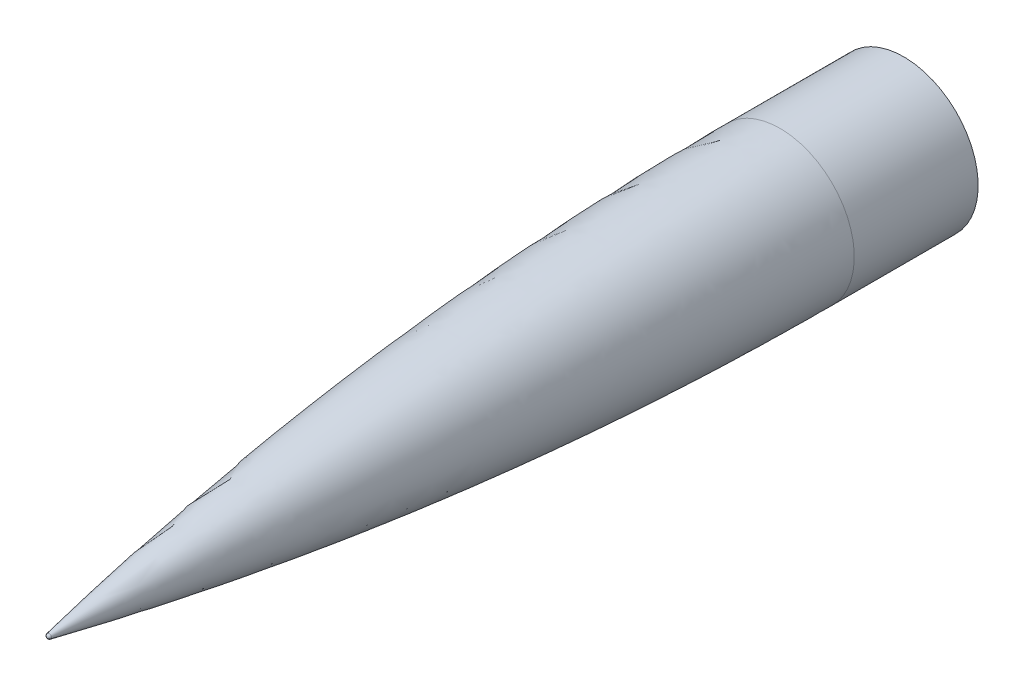
SolidWorks part; units mm, degrees
ref_plane "Front Plane" through (0, 0, 0) normal (0, 0, 1) x (1, 0, 0)
ref_plane "Top Plane" through (0, 0, 0) normal (0, 1, 0) x (1, 0, 0)
ref_plane "Right Plane" through (0, 0, 0) normal (1, 0, 0) x (0, 0, -1)
sketch "Sketch1" plane through (0, 0, 0) normal (1, 0, 0) x (0, 0, -1)
  line L0 (762, 76.2) -> (762, 0)
  line L3 (10.3925, 0) -> (762, 0)
  arc A0 (12.4378, 2.4913) -> (10.3925, 0) centre (12.9325, 0) ccw
  spline S0 degree 4 poles (-61.0191, -12.8425) (-59.4737, -12.5042) (-56.3822, -11.8291) (-51.7403, -10.8208) (-45.5583, -9.4885) (-39.3862, -8.1692) (-33.2692, -6.8717) (-27.1226, -5.5791) (-21.1084, -4.3233) (-14.8868, -3.0366) (-9.0602, -1.8385) (-2.4605, -0.4972) (2.6335, 0.5349) (10.3044, 2.0681) (13.7813, 2.7591) (20.1335, 4.0133) (25.0658, 4.9788) (30.0625, 5.9501) (35.1365, 6.9298) (40.175, 7.8954) (45.2236, 8.856) (50.3004, 9.815) (56.6964, 11.0143) (63.1226, 12.2072) (76.0348, 14.5797) (105.7552, 19.9151) (179.5351, 32.4336) (309.5135, 51.0954) (458.5062, 66.0207) (592.2627, 73.2972) (680.2011, 75.4371) (711.0499, 75.8648) (716.3009, 75.9293) (720.2108, 75.9737) (724.0925, 76.0143) (728.6024, 76.0565) (733.7414, 76.0977) (738.8715, 76.132) (744.039, 76.1594) (749.1296, 76.18) (754.1547, 76.1937) (760.6285, 76.2009) (764.1714, 76.2004) (771.986, 76.1908) (777.1794, 76.1708) (783.9054, 76.1407) (789.8483, 76.1007) (796.194, 76.0506) (802.3313, 75.9905) (808.6051, 75.92) (814.8509, 75.8391) (821.155, 75.7475) (827.4713, 75.6451) (832.2156, 75.5605) (835.3759, 75.5007) (836.956, 75.4699) knots 0 0 0 0 0 0.006999 0.013998 0.020997 0.027996 0.034868 0.041741 0.048613 0.055485 0.062358 0.06923 0.076103 0.082975 0.088656 0.094338 0.100019 0.105701 0.111382 0.117063 0.122745 0.128426 0.134233 0.145846 0.151652 0.186491 0.267783 0.476818 0.732306 0.848437 0.86005 0.865857 0.86876 0.871663 0.877345 0.883026 0.888707 0.894389 0.90007 0.905751 0.911433 0.917114 0.923979 0.930844 0.937709 0.944574 0.951439 0.958304 0.965169 0.972034 0.979026 0.986017 0.993009 1 1 1 1 1 construction
  spline S1 degree 4 poles (12.4378, 2.4913) (13.4887, 2.7001) (15.6066, 3.1195) (20.1335, 4.0133) (25.0658, 4.9788) (30.0625, 5.9501) (35.1365, 6.9298) (40.175, 7.8954) (45.2236, 8.856) (50.3004, 9.815) (56.6964, 11.0143) (63.1226, 12.2072) (76.0348, 14.5797) (105.7552, 19.9151) (179.5351, 32.4336) (309.5135, 51.0954) (458.5062, 66.0207) (592.2627, 73.2972) (680.2011, 75.4371) (711.0499, 75.8648) (716.3009, 75.9293) (720.2108, 75.9737) (724.0925, 76.0143) (728.6024, 76.0565) (733.7414, 76.0977) (738.8715, 76.132) (744.039, 76.1594) (749.1296, 76.18) (754.1547, 76.1937) (758.7697, 76.1989) (760.9285, 76.2) (762, 76.2) knots 0.082975 0.082975 0.082975 0.082975 0.082975 0.088656 0.094338 0.100019 0.105701 0.111382 0.117063 0.122745 0.128426 0.134233 0.145846 0.151652 0.186491 0.267783 0.476818 0.732306 0.848437 0.86005 0.865857 0.86876 0.871663 0.877345 0.883026 0.888707 0.894389 0.90007 0.905751 0.911433 0.917114 0.917114 0.917114 0.917114 0.917114
  dimension "D1" = 2.54
ref_axis "Axis1" through (0, 0, -480.06) along (0, 0, 1)
revolve "Revolve1" add sketch "Sketch1" angle 360 about axis through (0, 0, -480.06) along (0, 0, 1)
sketch "Sketch4" plane through (0, 0, -762) normal (0, 0, -1) x (-1, 0, 0)
  circle A0 centre (0, 0) radius 76.2
  dimension "D1" = 152.4
extrude "Boss-Extrude1" add sketch "Sketch4" along normal blind 127
equation "\"BodyTubeRadius\"= 3in"
equation "\"OgiveRatio\" = 5"
equation "\"OgiveRadius\"= ( \"BodyTubeRadius\" ^ 2 + ( \"OgiveLength\" ) ^ 2 ) / ( 2 * \"BodyTubeRadius\" )"
equation "\"OgiveLength\"= 2 * \"BodyTubeRadius\" * \"OgiveRatio\""
equation "\"noseRadius\" = .1in"
equation "\"noseCapCenter\"= \"OgiveLength\" - sqr ( ( \"OgiveRadius\" - \"noseRadius\" ) ^ 2 - ( \"OgiveRadius\" - \"BodyTubeRadius\" ) ^ 2 )'center of the sphere that forms that cap"
equation "\"yTangent\"= ( \"noseRadius\" * ( \"OgiveRadius\" - \"BodyTubeRadius\" ) ) / ( \"OgiveRadius\" - \"noseRadius\" )'y location of tangency"
equation "\"xTangent\"= \"noseCapCenter\" - sqr ( \"noseRadius\" ^ 2 - \"yTangent\" ^ 2 )'x location of tangency"
equation "\"D1@Sketch4\"=\"BodyTubeRadius\"*2"
equation "\"BodyTubeLength\"= 5in"
equation "\"D1@Sketch1\"=\"noseRadius\""
